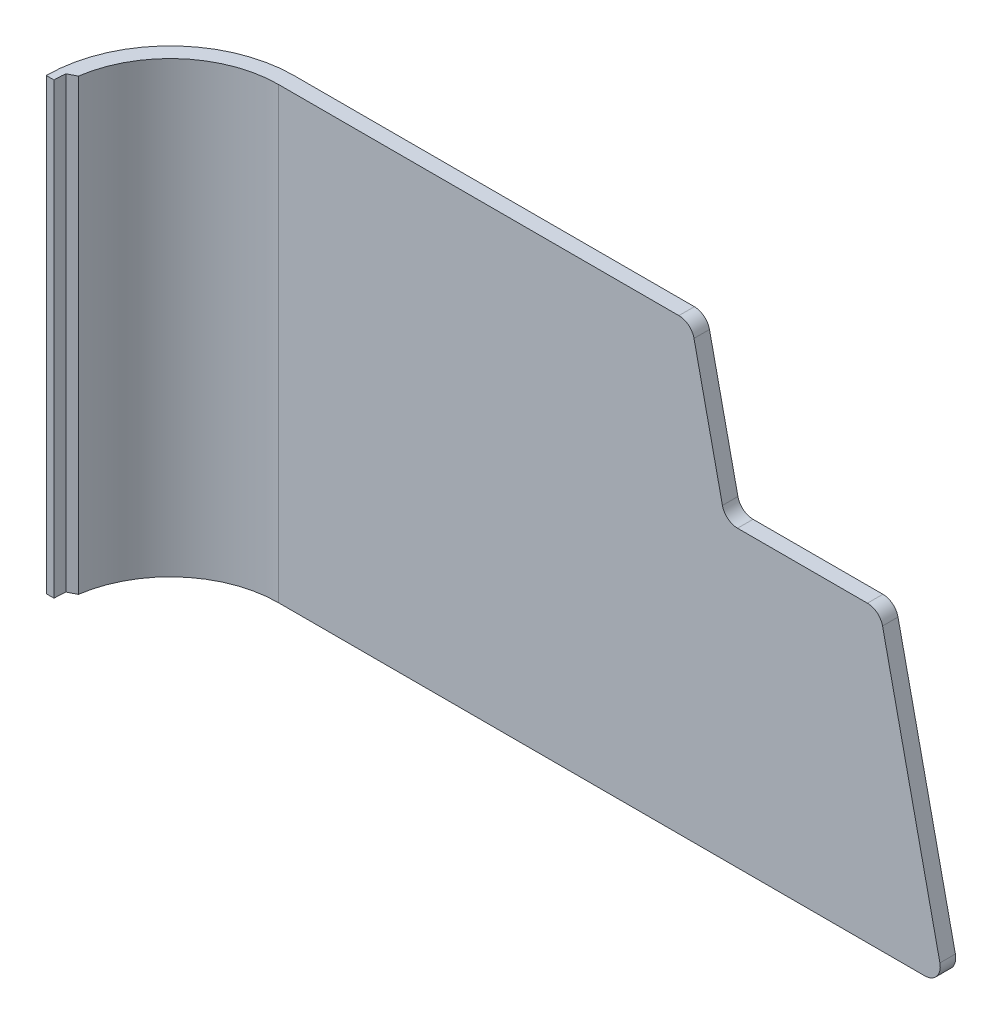
SolidWorks part; units mm, degrees
material "PVC 0.007 Plasticized"
ref_plane "Front Plane" through (0, 0, 0) normal (0, 0, 1) x (1, 0, 0)
ref_plane "Top Plane" through (0, 0, 0) normal (0, 1, 0) x (1, 0, 0)
ref_plane "Right Plane" through (0, 0, 0) normal (1, 0, 0) x (0, 0, -1)
sketch "Sketch1" plane through (0, 0, 0) normal (0, 1, 0) x (1, 0, 0)
  line L0 (61.8667, 0) -> (-71.7128, 0) construction
  line L2 (-50, 16) -> (36, 16)
  line L5 (36, 16) -> (36, 14)
  line L7 (-50, 14) -> (36, 14)
  line L8 (-50, -14) -> (34, -14) construction
  line L9 (-50, 14) -> (34, 14) construction
  line L10 (34, 14) -> (34, -14) construction
  line L11 (36, -14) -> (36, -16)
  line L12 (36, 16) -> (36, -16) construction
  line L13 (-64.9287, 1.4612) -> (-63.8564, 2)
  line L14 (-66, 0) -> (-65, 0)
  line L16 (-50, -16) -> (36, -16) construction
  arc A0 (-50, 16) -> (-66, 0) centre (-50, 0) ccw
  arc A1 (-50, 14) -> (-63.8564, 2) centre (-50, 0) ccw
  arc A2 (-64.9287, 1.4612) -> (-65, 0) centre (-50, 0) ccw
  arc A4 (-50, 14) -> (-50, -14) centre (-50, 0) ccw construction
  arc A5 (-50, 16) -> (-50, -16) centre (-50, 0) ccw construction
  dimension "D6" = 2
  dimension "D2" = 15
  dimension "D3" = 16
  dimension "D1" = 86
  dimension "D4" = 2
  dimension "D7" = 1.2
extrude "Boss-Extrude1" add sketch "Sketch1" along normal blind 58 contours A0 L14 A2 L13 A1 L7 L5 L2
sketch "Sketch2" plane through (0, 0, -14) normal (0, 0, 1) x (1, 0, 0)
  line L0 (12.8757, 58) -> (36, 58)
  line L1 (-50, 58) -> (36, 58) construction
  line L2 (36, 58) -> (36, 0)
  line L3 (36, 0) -> (27.7147, 38)
  line L4 (27.7147, 38) -> (7.7147, 38)
  line L5 (7.7147, 38) -> (3.354, 58)
  line L6 (-50, 0) -> (36, 0) construction
  line M5 (36, 0) -> (36, 58)
  line M6 (36, 58) -> (-50, 58)
  dimension "D1" = 20
  dimension "D2" = 102.3
  dimension "D3" = 38
extrude "Cut-Extrude2" cut sketch "Sketch2" against normal blind 2 contours L5 L4 L3 M5 M6
fillet "Fillet1" radius 2 4 edges at (36, 0, -15) (27.7147, 38, -15) (7.7147, 38, -15) (3.354, 58, -15)
